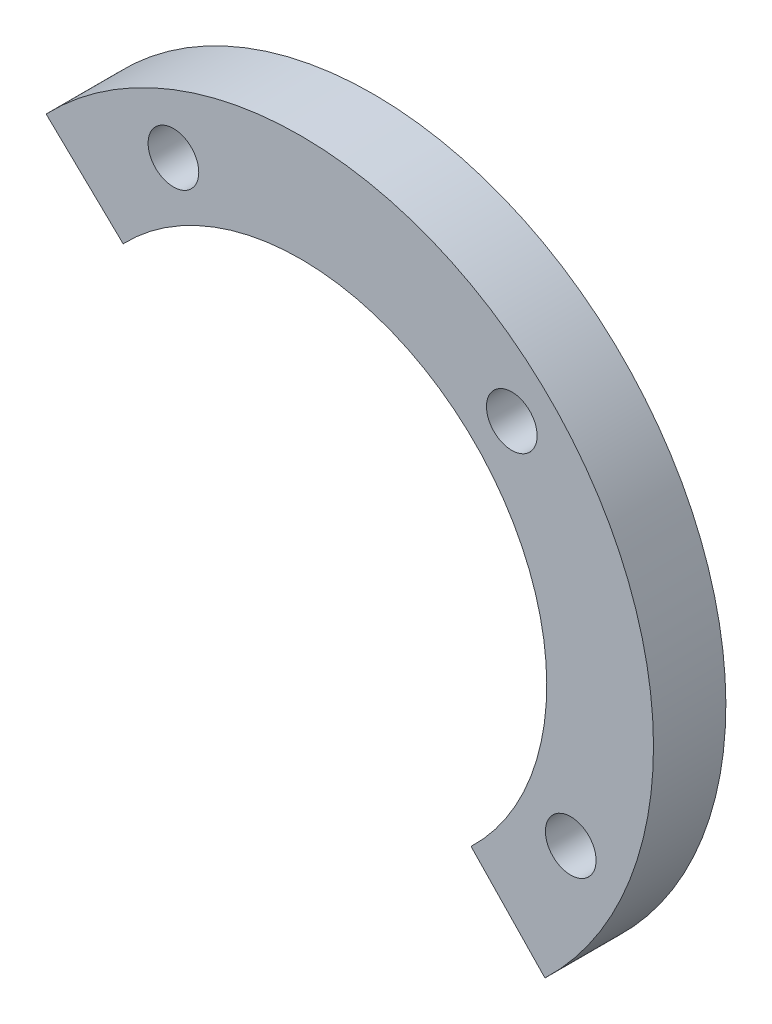
SolidWorks part; units mm, degrees
ref_plane "Front Plane" through (0, 0, 0) normal (0, 0, 1) x (1, 0, 0)
ref_plane "Top Plane" through (0, 0, 0) normal (0, 1, 0) x (1, 0, 0)
ref_plane "Right Plane" through (0, 0, 0) normal (1, 0, 0) x (0, 0, -1)
sketch "Sketch1" plane through (0, 0, 0) normal (0, 0, 1) x (1, 0, 0)
  line L0 (78.5, 50.9288) -> (74.4154, 55.1862)
  line L2 (50.9288, 78.5) -> (55.1862, 74.4154)
  arc A0 (78.5, 50.9288) -> (50.9288, 78.5) centre (65, 65) ccw construction
  arc A1 (78.5, 50.9288) -> (50.9288, 78.5) centre (65, 65) ccw
  circle A2 centre (57.9654, 79.9253) radius 1.4 construction
  circle A3 centre (76.6673, 76.6673) radius 1.4 construction
  circle A4 centre (79.9253, 57.9654) radius 1.4 construction
  circle A5 centre (57.9654, 79.9253) radius 1.4
  circle A6 centre (76.6673, 76.6673) radius 1.4
  circle A7 centre (79.9253, 57.9654) radius 1.4
  circle A8 centre (65, 65) radius 13.6
  circle A9 centre (65, 65) radius 13.5 construction
  dimension "D1" = 0.1
extrude "Shape" add sketch "Sketch1" along normal blind 4 contours A8 L0 A1 L2 A7 A6 A5
sketch "Sketch2" plane through (0, 0, 0) normal (0, 0, 1) x (1, 0, 0)
  line L0 (53.0575, 76.4577) -> (57.9654, 79.9253) construction
  line L1 (60.5766, 81.156) -> (58.2051, 82.8021)
  line L2 (58.2051, 82.8021) -> (55.5939, 81.5713)
  line L3 (55.5939, 81.5713) -> (55.3541, 78.6945)
  line L4 (55.3541, 78.6945) -> (57.7256, 77.0485)
  line L5 (57.7256, 77.0485) -> (60.3368, 78.2792)
  line L6 (60.3368, 78.2792) -> (60.5766, 81.156)
  line L7 (50.9288, 78.5) -> (55.1862, 74.4154) construction
  line L8 (50.3791, 79.6662) -> (62.9936, 85.6117) construction
  line L9 (57.9654, 79.9253) -> (56.6864, 82.639) construction
  line L10 (55.5939, 81.5713) -> (55.3807, 82.0236) construction
  line L11 (58.2051, 82.8021) -> (57.992, 83.2543) construction
  line L12 (57.9654, 79.9253) -> (76.6673, 76.6673) construction
  line L13 (50.9288, 78.5) -> (50.3791, 79.6662) construction
  line L14 (62.9936, 85.6117) -> (63.5433, 84.4455) construction
  line L15 (55.3541, 78.6945) -> (60.5766, 81.156) construction
  circle A0 centre (57.9654, 79.9253) radius 2.5 construction
  arc A1 (78.5, 50.9288) -> (50.9288, 78.5) centre (65, 65) ccw construction
  circle A2 centre (56.2587, 79.1209) radius 1
  circle A3 centre (56.4154, 81.0011) radius 1
  circle A4 centre (58.1221, 81.8055) radius 1
  circle A5 centre (59.6721, 80.7297) radius 1
  circle A6 centre (59.5153, 78.8494) radius 1
  circle A7 centre (57.8087, 78.045) radius 1
  point P21 (0, 0)
  point P28 (0, 0)
  point P39 (57.9654, 79.9253)
  dimension "D2" = 2
  dimension "D1" = 5
  dimension "D3" = 6
extrude "Nut cuts" cut sketch "Sketch2" along normal blind 2 contours A3 | A4 | A5 | A6 | A7 | A2 | L5 L6 L1 L2 L3 L4
